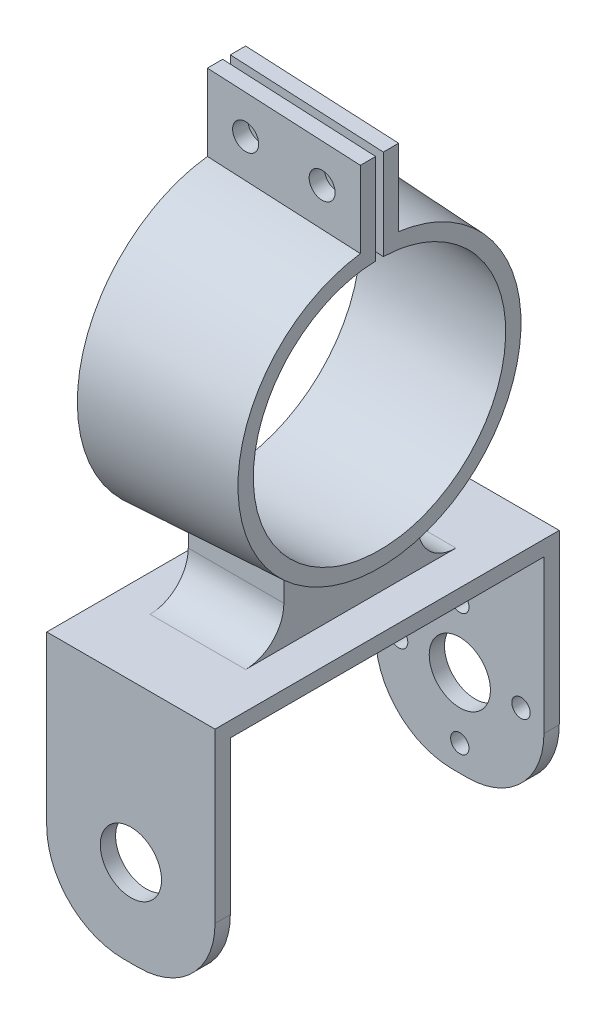
SolidWorks part; units mm, degrees
ref_plane "Front Plane" through (0, 0, 0) normal (0, 0, 1) x (1, 0, 0)
ref_plane "Top Plane" through (0, 0, 0) normal (0, 1, 0) x (1, 0, 0)
ref_plane "Right Plane" through (0, 0, 0) normal (1, 0, 0) x (0, 0, -1)
sketch "Sketch1" plane through (0, 0, 0) normal (1, 0, 0) x (0, 0, -1)
  line L0 (-2.5, 19.3391) -> (-2.5, 29.3391)
  line L1 (-2.5, 29.3391) -> (-0.5024, 29.3391)
  line L2 (2.5, 29.3391) -> (2.5, 19.3391)
  line L3 (-0.5024, 29.3391) -> (-0.5024, 17.4928)
  line L4 (0.5024, 29.3391) -> (0.5024, 17.4928)
  line L5 (0.5024, 29.3391) -> (2.5, 29.3391)
  line L6 (0.5024, 29.3391) -> (-0.5024, 29.3391) construction
  arc A0 (-0.5024, 17.4928) -> (0.5024, 17.4928) centre (0, 0) ccw
  arc A1 (-2.5, 19.3391) -> (2.5, 19.3391) centre (0, 0) ccw
  point P1 (0, 29.3391)
  dimension "D1" = 35
  dimension "D2" = 2
  dimension "D3" = 5
  dimension "D4" = 1.9976
  dimension "D5" = 10
ref_plane "Plane1" through (20, 0, 0) normal (1, 0, 0) x (0, 0, -1)
sketch "Sketch2" plane through (20, 0, 0) normal (1, 0, 0) x (0, 0, -1)
  line L0 (-2.5, 18.3326) -> (-2.5, 28.3326)
  line L1 (-2.5, 28.3326) -> (-0.5, 28.3326)
  line L2 (-0.5, 28.3326) -> (-0.5, 16.4924)
  line L3 (0.5, 16.4924) -> (0.5, 28.3326)
  line L4 (0.5, 28.3326) -> (2.5, 28.3326)
  line L5 (2.5, 28.3326) -> (2.5, 18.3326)
  line L6 (-0.5, 28.3326) -> (0.5, 28.3326) construction
  arc A0 (-0.5, 16.4924) -> (0.5, 16.4924) centre (0, 0) ccw
  arc A1 (-2.5, 18.3326) -> (2.5, 18.3326) centre (0, 0) ccw
  point P3 (2.5, 18.1723)
  point P10 (0, 28.3326)
  dimension "D1" = 33
  dimension "D2" = 2.0023
  dimension "D3" = 2
  dimension "D4" = 1
  dimension "D5" = 10
loft "Loft1" add profiles "Sketch2", "Sketch1"
sketch "Sketch3" plane through (0, 0, -2.5) normal (0, 0, -1) x (-1, 0, 0)
  line L0 (-15, 23.5779) -> (-5, 24.0811) construction
  line L1 (-20, 28.3326) -> (0, 29.3391) construction
  circle A0 centre (-15, 23.5779) radius 1.7
  circle A1 centre (-5, 24.0811) radius 1.7
  point P4 (-10, 23.8295)
  point P7 (-10, 28.8358)
  point P10 (-17.0185, 22.5682)
  dimension "D1" = 3.4
  dimension "D2" = 3.4
  dimension "D3" = 10
  dimension "D4" = 5
extrude "Cut-Extrude1" cut sketch "Sketch3" against normal blind 10
ref_plane "Plane2" through (0, -25, 0) normal (0, 1, 0) x (1, 0, 0)
sketch "Sketch4" plane through (0, -25, 0) normal (0, 1, 0) x (1, 0, 0)
  line L0 (20, 0) -> (0, 0) construction
  line L1 (21, 22.5) -> (-1, 22.5)
  line L2 (21, 22.5) -> (21, -22.5)
  line L3 (21, -22.5) -> (-1, -22.5)
  line L4 (-1, 22.5) -> (-1, -22.5)
  line L5 (10, -22.5) -> (10, 22.5) construction
  line L6 (21, 0) -> (-1, 0) construction
  line L7 (20, -18.5023) -> (20, 18.5023) construction
  point P4 (22.4819, 0)
  point P5 (10, 0)
  point P244 (10, 0)
  dimension "D1" = 22
  dimension "D2" = 45
extrude "Boss-Extrude1" add sketch "Sketch4" against normal blind 2 separate body
sketch "Sketch6" plane through (0, -25, 0) normal (0, 1, 0) x (1, 0, 0)
  line L0 (20, 0) -> (0, 0) construction
  line L1 (16.25, 8.75) -> (3.75, 8.75)
  line L2 (16.25, 8.75) -> (16.25, -8.75)
  line L3 (16.25, -8.75) -> (3.75, -8.75)
  line L4 (3.75, 8.75) -> (3.75, -8.75)
  line L5 (10, -8.75) -> (10, 8.75) construction
  line L6 (16.25, 0) -> (3.75, 0) construction
  line L7 (20, -18.5023) -> (20, 18.5023) construction
  point P4 (0, 0)
  point P9 (10, 0)
  point P264 (10, 0)
  dimension "D1" = 12.5
  dimension "D2" = 17.5
extrude "Boss-Extrude3" add sketch "Sketch6" along normal up to body
sketch "Sketch7" plane through (0, -27, 0) normal (0, -1, 0) x (1, 0, 0)
  line L0 (21, 22.5) -> (21, -22.5) construction
  line L1 (-1, 22.5) -> (21, 22.5)
  line L2 (-1, 22.5) -> (-1, 20.5)
  line L3 (-1, 20.5) -> (21, 20.5)
  line L4 (21, 22.5) -> (21, 20.5)
  line L5 (10, 20.5) -> (10, 22.5) construction
  line L6 (-1, 21.5) -> (21, 21.5) construction
  line L8 (-1, -22.5) -> (21, -22.5)
  line L9 (-1, -22.5) -> (-1, -20.5)
  line L10 (-1, -20.5) -> (21, -20.5)
  line L11 (21, -22.5) -> (21, -20.5)
  line L12 (10, -20.5) -> (10, -22.5) construction
  line L13 (-1, -21.5) -> (21, -21.5) construction
  point P206 (10, -21.5)
  point P260 (10, 21.5)
  dimension "D1" = 2
  dimension "D2" = 2
extrude "Boss-Extrude4" add sketch "Sketch7" along normal blind 30
sketch "Sketch8" plane through (0, 0, 22.5) normal (0, 0, 1) x (1, 0, 0)
  line L0 (-1, -25) -> (21, -25) construction
  circle A0 centre (10, -45.5913) radius 4
  point P2 (0, 0)
  point P5 (10, -25)
  dimension "D1" = 8
extrude "Cut-Extrude2" cut sketch "Sketch8" against normal through all
sketch "Sketch9" plane through (0, 0, -22.5) normal (0, 0, -1) x (-1, 0, 0)
  line L0 (1, -57) -> (-21, -57) construction
  circle A0 centre (-10, -37.5913) radius 1.2
  circle A1 centre (-2, -45.5913) radius 1.2
  circle A2 centre (-10, -53.5913) radius 1.2
  circle A3 centre (-18, -45.5913) radius 1.2
  point P2 (0, 0)
  point P5 (-10, -57)
  point P6 (-10, -45.5913)
  point P14 (-10, -45.5913)
  dimension "D1" = 2.4
  dimension "D3" = 16
  dimension "D2" = 4
extrude "Cut-Extrude3" cut sketch "Sketch9" against normal blind 30
fillet "Fillet1" radius 10 4 edges at (-1, -57, 21.5) (21, -57, 21.5) (21, -57, -21.5) (-1, -57, -21.5)
fillet "Fillet2" radius 5 2 edges at (10, -25, -8.75) (10, -25, 8.75)
